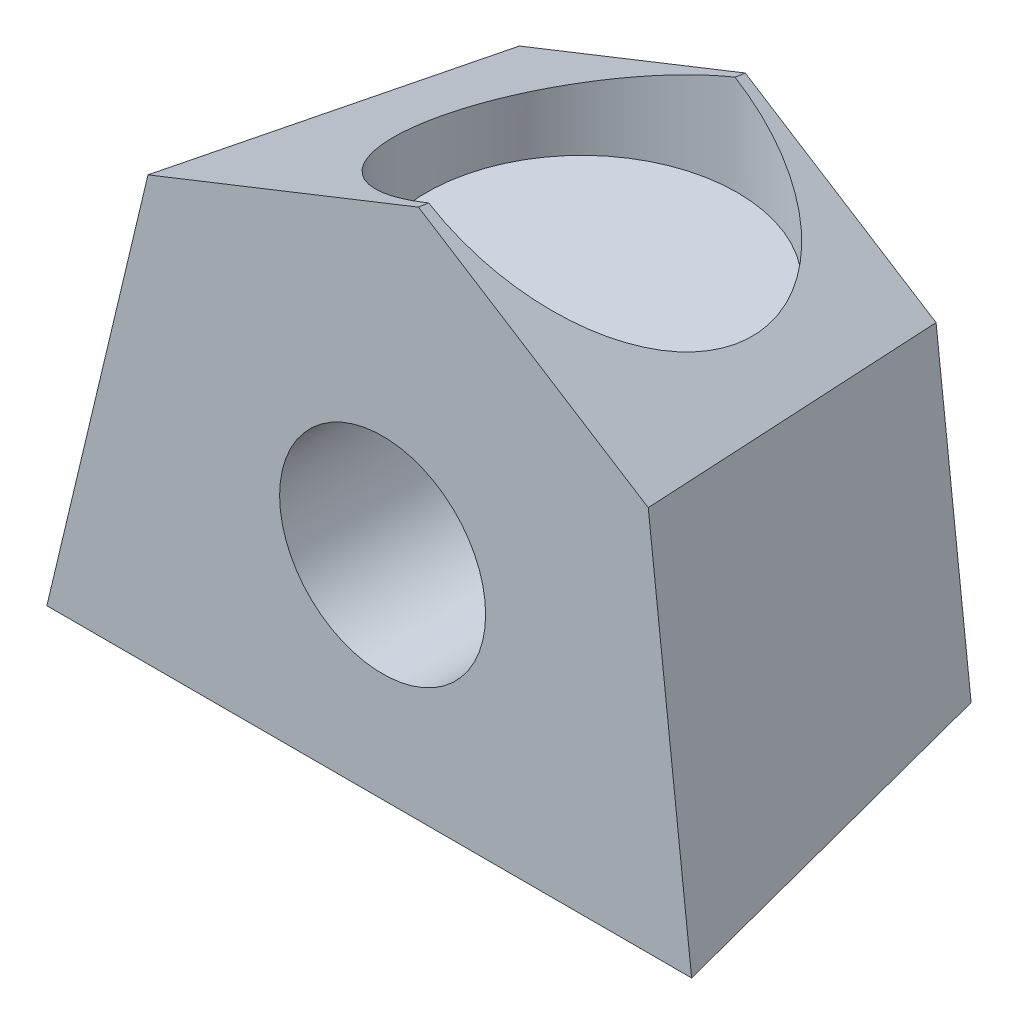
SolidWorks part; units mm, degrees
ref_plane "Front Plane" through (0, 0, 0) normal (0, 0, 1) x (1, 0, 0)
ref_plane "Top Plane" through (0, 0, 0) normal (0, 1, 0) x (1, 0, 0)
ref_plane "Right Plane" through (0, 0, 0) normal (1, 0, 0) x (0, 0, -1)
sketch "Sketch1" plane through (0, 0, 0) normal (0, 0, 1) x (1, 0, 0)
  line L0 (0, 0) -> (0, 83.7037) construction
  line L1 (0, 0) -> (125.1329, 0) construction
  line L2 (-53.266, 16.9098) -> (-36.9198, 23.392)
  line L3 (-36.9198, 23.392) -> (-23.1101, 14.6552)
  line L4 (-23.1101, 14.6552) -> (-20.5736, -7.8913)
  line L5 (-20.5736, -7.8913) -> (-59.1845, -7.8913)
  line L6 (-53.266, 16.9098) -> (-59.1845, -7.8913)
extrude "Boss-Extrude1" add sketch "Sketch1" along normal blind 24 draft 8 draft outward yes
scale "Scale1" scale about centroid uniform scaling yes scale factor 4
ref_plane "Plane2" through (0, 138, 0) normal (0, 1, 0) x (1, 0, 0)
sketch "Sketch3" plane through (0, 138, 0) normal (0, 1, 0) x (1, 0, 0)
  line L0 (-28.6161, -57.6452) -> (-30.0262, 38.3548) construction
  circle A0 centre (-29.3212, -9.6452) radius 45
  dimension "D1" = 90
extrude "Cut-Extrude1" cut sketch "Sketch3" against normal blind 88
sketch "Sketch4" plane through (0, 0, 57.6452) normal (0, 0, 1) x (1, 0, 0)
  line L0 (-121.5405, 0.8065) -> (43.5542, 0.8065) construction
  line L1 (-106.9059, 62.1325) -> (-136.1752, -60.5195) construction
  line L2 (50.4534, -60.5195) -> (37.8963, 51.0992) construction
  circle A0 centre (-38.9932, 0.8065) radius 29.815
  dimension "D1" = 59.63
extrude "Cut-Extrude2" cut sketch "Sketch4" against normal up to surface (96 mm away) up to face at (-36.7901, 15.8771, -38.3548)
